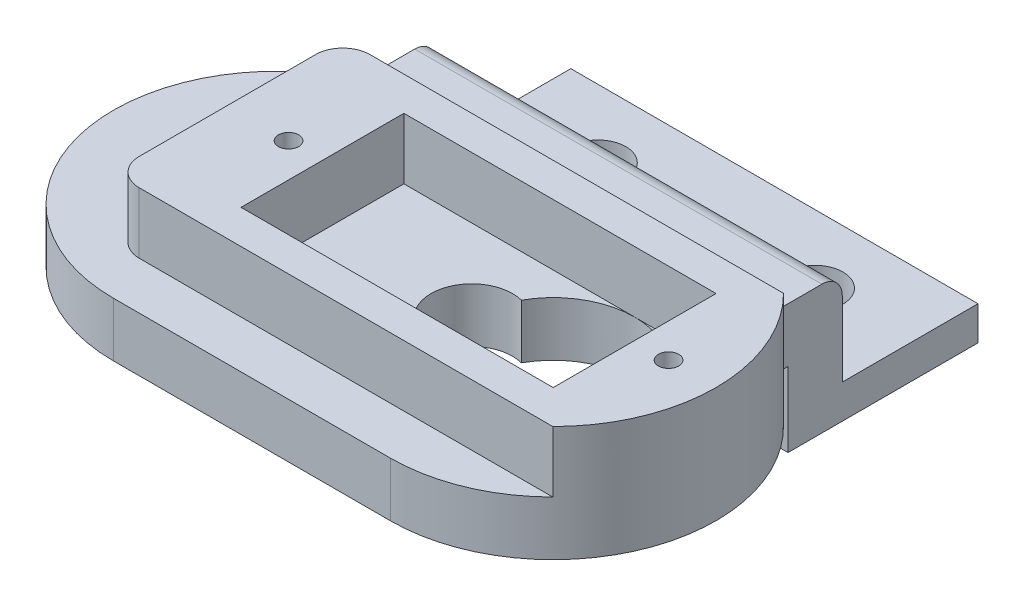
SolidWorks part; units mm, degrees
ref_plane "Plan de face" through (0, 0, 0) normal (0, 0, 1) x (1, 0, 0)
ref_plane "Plan de dessus" through (0, 0, 0) normal (0, 1, 0) x (1, 0, 0)
ref_plane "Plan de droite" through (0, 0, 0) normal (1, 0, 0) x (0, 0, -1)
sketch "Esquisse1" plane through (0, 0, 0) normal (0, 1, 0) x (1, 0, 0)
  line L0 (-37.4436, 0) -> (41.3534, 0) construction
  line L1 (0, 36.015) -> (0, -39.1729) construction
  line L2 (-27.3516, 16.5) -> (20.0902, 16.5) construction
  line L5 (-17.3734, -12) -> (19.183, -12) construction
  line L6 (-15, 10.9982) -> (-15, 16.5)
  line L7 (-15, 16.5) -> (15, 16.5)
  line L8 (-10.2, -12) -> (10.2, -12)
  line L9 (15, 10.9982) -> (15, 16.5)
  line L10 (-23.2701, 12) -> (28.1629, 12) construction
  arc A1 (-10.2, -12) -> (-15, 10.9982) centre (-10.2, 0) cw
  arc A2 (10.2, -12) -> (15, 10.9982) centre (10.2, 0) ccw
  point P14 (0, -12)
  point P19 (0, 16.5)
  dimension "D2" = 12
  dimension "D1" = 12
  dimension "D3" = 12
  dimension "D4" = 10.2
  dimension "D5" = 15
  dimension "D6" = 4.5
extrude "Boss.-Extru.1" add sketch "Esquisse1" along normal blind 4
sketch "Esquisse2" plane through (0, 0, 0) normal (0, -1, 0) x (1, 0, 0)
  line L2 (-15, -10.9982) -> (-15, -16.5)
  line L3 (-15, -10.9982) -> (-15, -16.5)
  line L8 (10.2, 12) -> (-10.2, 12)
  line L10 (10.2, 12) -> (-10.2, 12)
  line L12 (-15, -16.5) -> (15, -16.5)
  line L13 (-15, -16.5) -> (15, -16.5)
  line L14 (15, -16.5) -> (15, -10.9982)
  line L15 (15, -16.5) -> (15, -10.9982)
  circle A0 centre (-10.2, 0) radius 3.75
  arc A2 (-10.2, 12) -> (-15, -10.9982) centre (-10.2, 0) ccw
  arc A8 (-10.2, 12) -> (-15, -10.9982) centre (-10.2, 0) ccw
  arc A10 (15, -10.9982) -> (10.2, 12) centre (10.2, 0) ccw
  arc A11 (15, -10.9982) -> (10.2, 12) centre (10.2, 0) ccw
  dimension "D3" = 7.5
  dimension "D1" = 0
extrude "Boss.-Extru.2" add sketch "Esquisse2" along normal blind 5.5
sketch "Esquisse3" plane through (0, -5.5, 0) normal (0, -1, 0) x (1, 0, 0)
  circle A0 centre (-10.2, 0) radius 2.5
  circle A1 centre (-10.2, 0) radius 3.75
  circle A4 centre (-10.2, 0) radius 3.75
  dimension "D2" = 5
  dimension "D1" = 0
extrude "Boss.-Extru.3" add sketch "Esquisse3" along normal blind 2 contours A0
sketch "Esquisse5" plane through (0, 4, 0) normal (0, 1, 0) x (1, 0, 0)
  line L0 (-10.2, 0) -> (10.2, 0) construction
  line L2 (15, 16.5) -> (-15, 16.5)
  line L6 (4.95, 1.9019) -> (4.95, -6.1846) construction
  line L23 (15, 16.5) -> (-15, 16.5)
  line L27 (-10.2, -12) -> (10.2, -12)
  line L29 (-10.2, -12) -> (10.2, -12)
  line L31 (-15, 16.5) -> (-15, 10.9982)
  line L32 (-15, 16.5) -> (-15, 10.9982)
  line L33 (15, 10.9982) -> (15, 16.5)
  line L34 (15, 10.9982) -> (15, 16.5)
  arc A7 (4.95, 2.9047) -> (4.95, -2.9047) centre (10.2, 0) cw
  arc A8 (4.95, 2.9047) -> (4.95, -2.9047) centre (10.2, 0) ccw construction
  arc A9 (4.95, 2.9047) -> (4.95, -2.9047) centre (4.2, 0) ccw
  arc A13 (-15, 10.9982) -> (-10.2, -12) centre (-10.2, 0) ccw
  arc A16 (-15, 10.9982) -> (-10.2, -12) centre (-10.2, 0) ccw
  arc A18 (10.2, -12) -> (15, 10.9982) centre (10.2, 0) ccw
  arc A19 (10.2, -12) -> (15, 10.9982) centre (10.2, 0) ccw
  dimension "D2" = 4.95
  dimension "D4" = 6
  dimension "D5" = 3
  dimension "D1" = 0
extrude "Enlèv. mat.-Extru.2" cut sketch "Esquisse5" against normal through all contours A7 A9
sketch "Esquisse6" plane through (0, 4, 0) normal (0, 1, 0) x (1, 0, 0)
  line L0 (16.2, -6) -> (-6.8, -6)
  line L1 (-5.7504, 21.1232) -> (-5.8242, 21.1232)
  line L2 (15, 16.5) -> (-15, 16.5)
  line L6 (10.2, 6) -> (-6.8, 6) construction
  line L7 (-6.8, 6) -> (16.2, 6)
  line L8 (16.2, -6) -> (16.2, 6)
  line L9 (-6.8, -6) -> (-6.8, 6)
  line L10 (-13.8, 6.5) -> (-13.8, -6.5)
  line L11 (-11.8, -8.5) -> (18.6705, -8.5)
  line L13 (18.6705, 8.5) -> (-11.8, 8.5)
  line L16 (15, 16.5) -> (-15, 16.5)
  line L24 (-10.2, -12) -> (10.2, -12)
  line L26 (-10.2, -12) -> (10.2, -12)
  line L27 (-15, 16.5) -> (-15, 10.9982)
  line L28 (-15, 16.5) -> (-15, 10.9982)
  line L29 (15, 10.9982) -> (15, 16.5)
  line L30 (15, 10.9982) -> (15, 16.5)
  arc A0 (4.95, -2.9047) -> (4.95, 2.9047) centre (10.2, 0) ccw construction
  arc A2 (-15, 10.9982) -> (-10.2, -12) centre (-10.2, 0) ccw
  arc A7 (18.6705, 8.5) -> (18.6705, -8.5) centre (10.2, 0) cw
  arc A8 (-13.8, -6.5) -> (-11.8, -8.5) centre (-11.8, -6.5) ccw
  arc A9 (-13.8, 6.5) -> (-11.8, 8.5) centre (-11.8, 6.5) cw
  arc A11 (-15, 10.9982) -> (-10.2, -12) centre (-10.2, 0) ccw
  arc A14 (10.2, -12) -> (15, 10.9982) centre (10.2, 0) ccw
  arc A16 (10.2, -12) -> (15, 10.9982) centre (10.2, 0) ccw
  point P20 (16.2, 0)
  dimension "D4" = 12
  dimension "D6" = 2
  dimension "D2" = 2.5
  dimension "D3" = 2.5
  dimension "23" = 23
  dimension "D5" = 7
  dimension "D1" = 0
extrude "Boss.-Extru.7" add sketch "Esquisse6" along normal blind 4.5
sketch "Esquisse7" plane through (0, 8.5, 0) normal (0, 1, 0) x (1, 0, 0)
  line L0 (-18.4642, 0) -> (22.2, 0) construction
  line L1 (-6.8, -6) -> (-6.8, 6) construction
  line L2 (16.2, -6) -> (16.2, 6) construction
  line L3 (18.6705, 8.5) -> (-11.8, 8.5)
  line L5 (-11.8, -8.5) -> (18.6705, -8.5)
  line L6 (18.6705, 8.5) -> (-11.8, 8.5)
  line L11 (-13.8, 6.5) -> (-13.8, -6.5)
  line L12 (-13.8, 6.5) -> (-13.8, -6.5)
  line L13 (-13.8, 6.5) -> (-13.8, -6.5)
  line L14 (-11.8, -8.5) -> (18.6705, -8.5)
  line L15 (18.6705, 8.5) -> (-11.8, 8.5)
  line L16 (-13.8, 6.5) -> (-13.8, -6.5)
  line L17 (-11.8, -8.5) -> (18.6705, -8.5)
  line L18 (18.6705, 8.5) -> (-11.8, 8.5)
  circle A0 centre (-9.3, 0) radius 0.75
  circle A3 centre (18.7, 0) radius 0.75
  arc A7 (-11.8, 8.5) -> (-13.8, 6.5) centre (-11.8, 6.5) ccw
  arc A8 (-11.8, 8.5) -> (-13.8, 6.5) centre (-11.8, 6.5) ccw
  arc A9 (-13.8, -6.5) -> (-11.8, -8.5) centre (-11.8, -6.5) ccw
  arc A10 (-13.8, -6.5) -> (-11.8, -8.5) centre (-11.8, -6.5) ccw
  arc A11 (18.6705, -8.5) -> (18.6705, 8.5) centre (10.2, 0) ccw
  arc A12 (18.6705, -8.5) -> (18.6705, 8.5) centre (10.2, 0) ccw
  arc A13 (-11.8, 8.5) -> (-13.8, 6.5) centre (-11.8, 6.5) ccw
  arc A14 (-13.8, -6.5) -> (-11.8, -8.5) centre (-11.8, -6.5) ccw
  arc A15 (18.6705, -8.5) -> (18.6705, 8.5) centre (10.2, 0) ccw
  arc A16 (-11.8, 8.5) -> (-13.8, 6.5) centre (-11.8, 6.5) ccw
  arc A17 (-13.8, -6.5) -> (-11.8, -8.5) centre (-11.8, -6.5) ccw
  arc A18 (18.6705, -8.5) -> (18.6705, 8.5) centre (10.2, 0) ccw
  dimension "D2" = 1.5
  dimension "1" = 1.5
  dimension "D3" = 2.5
  dimension "D4" = 0
  dimension "D5" = 2.5
  dimension "D1" = 0
extrude "Enlèv. mat.-Extru.3" cut sketch "Esquisse7" against normal blind 8 contours L0 A0 | A0 L0 | A3
sketch "Esquisse8" plane through (0, 0, 0) normal (0, -1, 0) x (1, 0, 0)
  line L0 (-15, -16.5) -> (15, -16.5)
  line L1 (-15, -12.5) -> (15, -12.5)
  line L4 (10.2, 12) -> (-10.2, 12)
  line L5 (-15, -10.9982) -> (-15, -16.5)
  line L6 (-15, -16.5) -> (15, -16.5)
  line L7 (15, -16.5) -> (15, -10.9982)
  line L8 (10.2, 12) -> (-10.2, 12)
  line L9 (-15, -10.9982) -> (-15, -16.5)
  line L11 (15, -16.5) -> (15, -10.9982)
  line L14 (-15, -16.5) -> (15, -16.5)
  arc A2 (15, -10.9982) -> (10.2, 12) centre (10.2, 0) ccw
  arc A3 (-10.2, 12) -> (-15, -10.9982) centre (-10.2, 0) ccw
  arc A4 (15, -10.9982) -> (10.2, 12) centre (10.2, 0) ccw
  arc A5 (-10.2, 12) -> (-15, -10.9982) centre (-10.2, 0) ccw
  line M11 (-15, -10.9982) -> (-15, -16.5)
  line M12 (-15, -16.5) -> (15, -16.5)
  line M13 (15, -16.5) -> (15, -10.9982)
  dimension "D2" = 4
  dimension "D1" = 0
extrude "Boss.-Extru.8" add sketch "Esquisse8" along normal blind 5.5 contours L0 M11 M12 M13 | L14 L11 A4 L8 A5 L9
sketch "Esquisse9" plane through (0, 0, -16.5) normal (0, 0, -1) x (-1, 0, 0)
  line L0 (-15, -3) -> (15, -3)
  line L4 (-15, 4) -> (-15, -5.5)
  line L5 (-15, -5.5) -> (15, -5.5)
  line L6 (15, -5.5) -> (15, 4)
  line L7 (-15, -5.5) -> (15, -5.5)
  line L8 (-15, 4) -> (-15, -5.5)
  line L10 (15, -5.5) -> (15, 4)
  line L13 (15, 4) -> (-15, 4)
  line L15 (15, 4) -> (-15, 4)
  line M6 (-15, 4) -> (-15, -5.5)
  line M7 (-15, -5.5) -> (15, -5.5)
  line M8 (15, -5.5) -> (15, 4)
  dimension "D2" = 2.5
  dimension "D1" = 0
extrude "Boss.-Extru.9" add sketch "Esquisse9" along normal blind 10 contours L0 M6 M7 M8
sketch "Esquisse10" plane through (0, -3, 0) normal (0, 1, 0) x (1, 0, 0)
  line L0 (0, 30.6935) -> (0, -13.0761) construction
  line L1 (-18.5633, 21.5) -> (20.8604, 21.5) construction
  line L6 (-15, 16.5) -> (15, 16.5)
  line L7 (15, 16.5) -> (15, 26.5)
  line L8 (15, 26.5) -> (-15, 26.5)
  line L9 (-15, 26.5) -> (-15, 16.5)
  line L11 (15, 16.5) -> (15, 26.5)
  line L12 (15, 26.5) -> (-15, 26.5)
  line L13 (-15, 26.5) -> (-15, 16.5)
  line L15 (-15, 16.5) -> (15, 16.5)
  circle A0 centre (-8, 21.5) radius 2.05
  circle A1 centre (8, 21.5) radius 2.05
  dimension "D1" = 0
  dimension "D3" = 4.1
  dimension "D2" = 8
extrude "Enlèv. mat.-Extru.4" cut sketch "Esquisse10" against normal through all contours A0 | A1
fillet "Congé2" radius 1.5 1 edges at (0, 4, -16.5)
